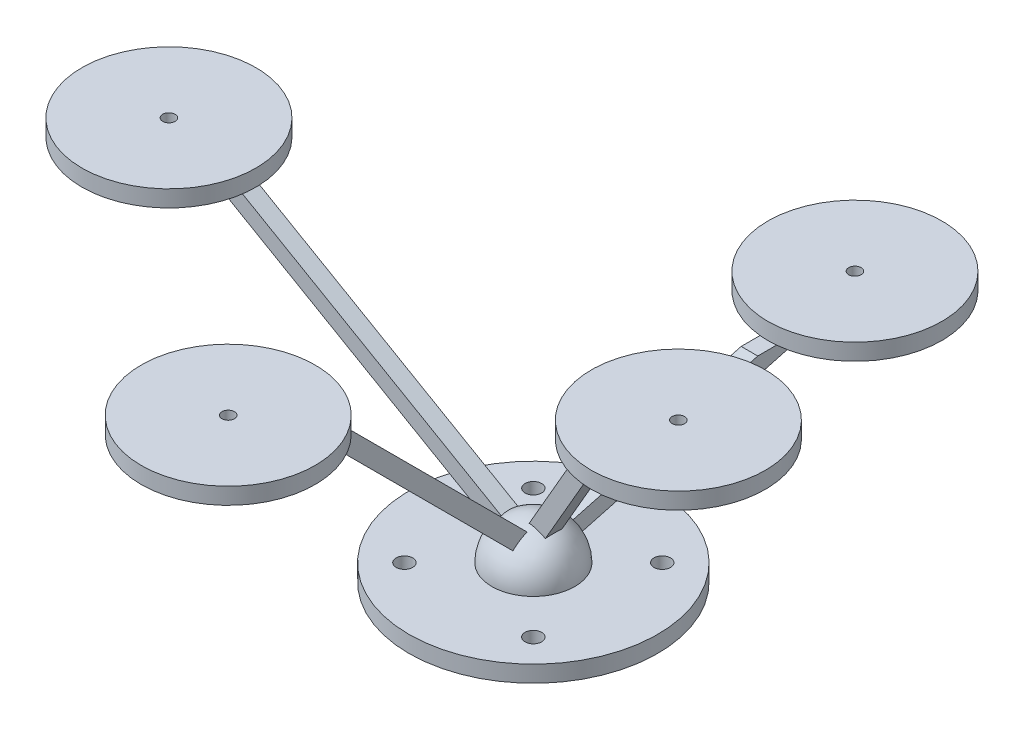
SolidWorks part; units mm, degrees
ref_plane "前视基准面" through (0, 0, 0) normal (0, 0, 1) x (1, 0, 0)
ref_plane "上视基准面" through (0, 0, 0) normal (0, 1, 0) x (1, 0, 0)
ref_plane "右视基准面" through (0, 0, 0) normal (1, 0, 0) x (0, 0, -1)
sketch "草图1" plane through (0, 0, 0) normal (0, 1, 0) x (1, 0, 0)
  line L0 (-23.4221, 0) -> (25.8766, 0) construction
  line L1 (0, 26.1921) -> (0, -25.0701) construction
  line L2 (-18.9498, 18.9498) -> (18.8862, -18.8862) construction
  line L3 (18.9424, 18.9424) -> (-20.2044, -20.2044) construction
  circle A0 centre (0, 0) radius 15
  circle A1 centre (0, 0) radius 11 construction
  circle A2 centre (7.7782, 7.7782) radius 1
  circle A3 centre (-7.7782, 7.7782) radius 1
  circle A4 centre (-7.7782, -7.7782) radius 1
  circle A5 centre (7.7782, -7.7782) radius 1
  dimension "D1" = 30
  dimension "D4" = 22
  dimension "D5" = 2
  dimension "D2" = 45
  dimension "D3" = 45
extrude "凸台-拉伸1" add sketch "草图1" along normal blind 2
sketch "草图2" plane through (0, 0, 0) normal (1, 0, 0) x (0, 0, -1)
  line L0 (0, 2) -> (0, 7)
  line L1 (15, 2) -> (-15, 2) construction
  line L2 (0, 2) -> (5, 2)
  arc A0 (0, 7) -> (5, 2) centre (0, 2) cw
  dimension "D1" = 5
revolve "旋转1" add sketch "草图2" angle 360 about L0
sketch "草图3" plane through (0, 0, 0) normal (0, 0, 1) x (1, 0, 0)
  line L0 (0, 2) -> (0, 9.7216) construction
  line L1 (15, 2) -> (-15, 2) construction
  line L2 (0, 2) -> (12.5, 23.6506)
  line L3 (8.7782, 2) -> (6.7782, 2) construction
  line L4 (0, 6) -> (10.1906, 23.6506)
  line L6 (10.1906, 23.6506) -> (12.5, 23.6506)
  line L7 (0, 2) -> (-38.9711, 24.5)
  line L8 (-34.9711, 24.5) -> (0, 4.3094)
  line L9 (0, 4.3094) -> (0, 6)
  line L10 (-38.9711, 24.5) -> (-34.9711, 24.5)
  dimension "D1" = 60
  dimension "D2" = 25
  dimension "D3" = 2
  dimension "D4" = 30
  dimension "D5" = 45
  dimension "D6" = 2
extrude "凸台-拉伸2" add sketch "草图3" along normal mid plane 2
sketch "草图4" plane through (0, 23.6506, 0) normal (0, 1, 0) x (1, 0, 0)
  line L0 (12.5, -1) -> (12.5, 1) construction
  circle A0 centre (17.5, 0) radius 10.5
  circle A1 centre (17.5, 0) radius 0.75
  dimension "D1" = 21
  dimension "D2" = 1.5
  dimension "D3" = 5
extrude "凸台-拉伸3" add sketch "草图4" along normal blind 2
sketch "草图5" plane through (0, 24.5, 0) normal (0, 1, 0) x (1, 0, 0)
  line L0 (-38.9711, -1) -> (-38.9711, 1) construction
  circle A0 centre (-43.9711, 0) radius 10.5
  circle A1 centre (-43.9711, 0) radius 0.75
  dimension "D1" = 21
  dimension "D2" = 1.5
  dimension "D3" = 5
extrude "凸台-拉伸4" add sketch "草图5" along normal blind 2
sketch "草图6" plane through (0, 0, 0) normal (1, 0, 0) x (0, 0, -1)
  line L0 (0, 0) -> (0, 10.6928) construction
  line L1 (0, 2) -> (33.8074, 11.0587)
  line L2 (15, 2) -> (-15, 2) construction
  line L3 (8.7782, 2) -> (6.7782, 2) construction
  line L4 (0, 4.0706) -> (26.08, 11.0587)
  line L5 (26.08, 11.0587) -> (33.8074, 11.0587)
  line L6 (0, 2) -> (-31.8198, 33.8198)
  line L7 (0, 4.8284) -> (-28.9914, 33.8198)
  line L8 (-31.8198, 33.8198) -> (-28.9914, 33.8198)
  line L9 (0, 4.8284) -> (0, 4.0706)
  dimension "D1" = 15
  dimension "D2" = 35
  dimension "D3" = 2
  dimension "D4" = 45
  dimension "D5" = 45
  dimension "D6" = 2
extrude "凸台-拉伸5" add sketch "草图6" along normal mid plane 2
sketch "草图7" plane through (0, 11.0587, 0) normal (0, 1, 0) x (1, 0, 0)
  line L0 (1, 33.8074) -> (-1, 33.8074) construction
  circle A0 centre (0, 38.8074) radius 10.5
  circle A1 centre (0, 38.8074) radius 0.75
  dimension "D1" = 21
  dimension "D2" = 1.5
  dimension "D3" = 5
extrude "凸台-拉伸6" add sketch "草图7" along normal blind 2
sketch "草图8" plane through (0, 33.8198, 0) normal (0, 1, 0) x (1, 0, 0)
  line L0 (1, -31.8198) -> (-1, -31.8198) construction
  circle A0 centre (0, -36.8198) radius 10.5
  circle A1 centre (0, -36.8198) radius 0.75
  dimension "D1" = 1.5
  dimension "D2" = 21
  dimension "D3" = 5
extrude "凸台-拉伸7" add sketch "草图8" along normal blind 2
